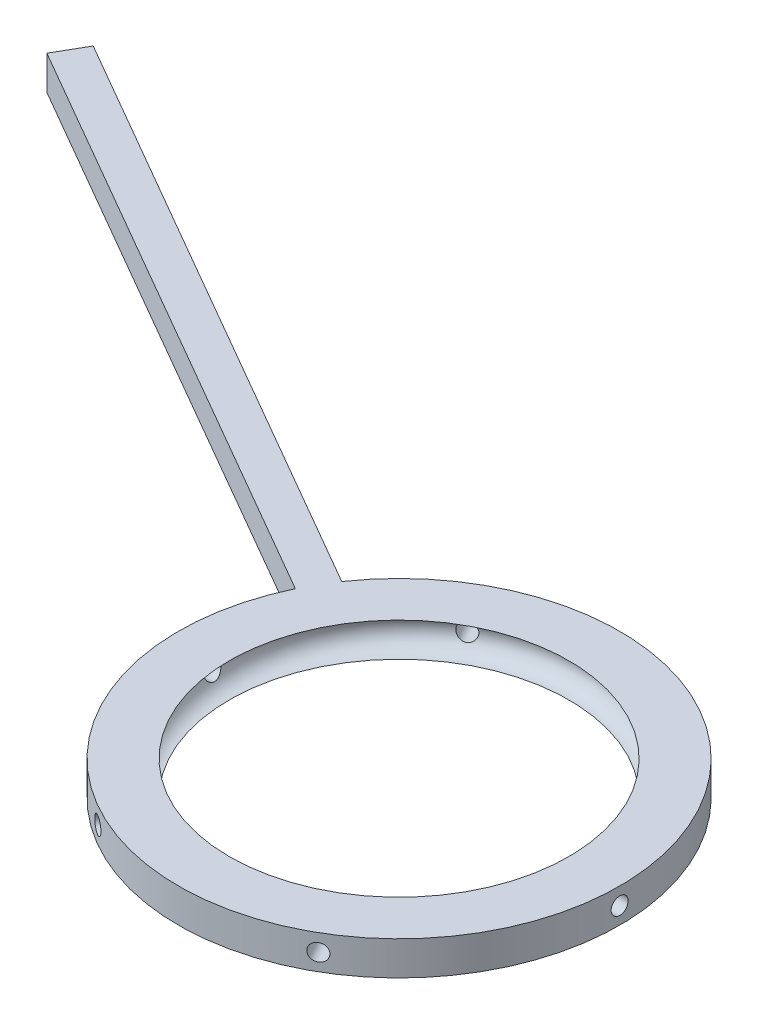
SolidWorks part; units mm, degrees
ref_plane "前视基准面" through (0, 0, 0) normal (0, 0, 1) x (1, 0, 0)
ref_plane "上视基准面" through (0, 0, 0) normal (0, 1, 0) x (1, 0, 0)
ref_plane "右视基准面" through (0, 0, 0) normal (1, 0, 0) x (0, 0, -1)
sketch "草图2" plane through (0, 0, 0) normal (0, 0, 1) x (1, 0, 0)
  line L0 (-500, -50) -> (-650, -50)
  line L1 (-650, -50) -> (-650, 50)
  line L2 (-650, 50) -> (-500, 50)
  line L3 (0, 223.3547) -> (0, -403.8715) construction
  arc A0 (-500, 50) -> (-500, -50) centre (-500, 0) ccw
  dimension "D2" = 100
  dimension "D1" = 500
  dimension "D3" = 150
revolve "旋转1" add sketch "草图2" angle 360 about L3
sketch "草图3" plane through (0, 0, 0) normal (0, 1, 0) x (1, 0, 0)
  circle A0 centre (0, 0) radius 550 construction
sketch "草图4" plane through (0, 0, 0) normal (1, 0, 0) x (0, 0, -1)
  circle A0 centre (0, 0) radius 25
extrude "切除-拉伸1" cut sketch "草图4" against normal blind 1435
pattern_circular "阵列(圆周)1" count 6 over 360 about axis through (0, 50, 0) along (0, 1, 0) of "切除-拉伸1"
sketch "草图5" plane through (0, 0, 0) normal (0, 1, 0) x (1, 0, 0)
  line L0 (0, 0) -> (730.9011, 421.986) construction
  line L1 (0, 0) -> (1057.1513, 0) construction
  line L2 (586.2486, 280.7358) -> (2318.2994, 1280.7358) construction
  line L3 (2268.2994, 1367.3383) -> (536.2486, 367.3383) construction
  line L4 (2268.2994, 1367.3383) -> (2318.2994, 1280.7358) construction
  line L5 (0, 976.5615) -> (0, -1167.5097) construction
  line L6 (-2268.2994, 1367.3383) -> (-2318.2994, 1280.7358)
  line L7 (-2268.2994, 1367.3383) -> (-536.2486, 367.3383)
  line L8 (-586.2486, 280.7358) -> (-2318.2994, 1280.7358)
  circle A0 centre (0, 0) radius 650
  dimension "D1" = 100
  dimension "D2" = 2000
  dimension "D3" = 30
  dimension "D4" = 30
  dimension "D5" = 50
extrude "凸台-拉伸1" add sketch "草图5" along normal mid plane 100 contours A0 L7 L6 L8
